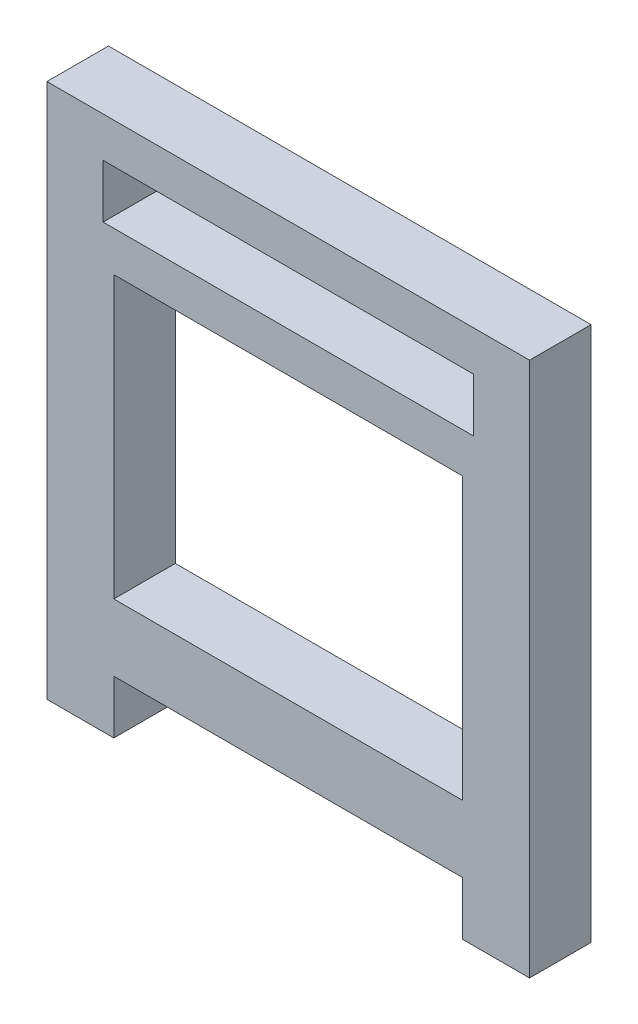
SolidWorks part; units mm, degrees
ref_plane "Front Plane" through (0, 0, 0) normal (0, 0, 1) x (1, 0, 0)
ref_plane "Top Plane" through (0, 0, 0) normal (0, 1, 0) x (1, 0, 0)
ref_plane "Right Plane" through (0, 0, 0) normal (1, 0, 0) x (0, 0, -1)
sketch "Sketch1" plane through (0, 0, 0) normal (0, 0, 1) x (1, 0, 0)
  line L0 (0, 0) -> (0, -2)
  line L1 (2.5, 0) -> (15.54, 0)
  line L2 (0, 0) -> (0, 18)
  line L3 (0, 18) -> (18.04, 18)
  line L4 (18.04, 0) -> (18.04, 18)
  line L5 (0, -2) -> (2.5, -2)
  line L6 (2.5, -2) -> (2.5, 0)
  line L7 (18.04, 0) -> (18.04, -2)
  line L8 (18.04, -2) -> (15.54, -2)
  line L9 (15.54, -2) -> (15.54, 0)
  line L12 (2.5, 2.5) -> (15.54, 2.5)
  line L13 (2.5, 2.5) -> (2.5, 13)
  line L14 (2.5, 13) -> (15.54, 13)
  line L15 (15.54, 2.5) -> (15.54, 13)
  line L16 (2.1, 14.5) -> (15.94, 14.5)
  line L17 (2.1, 14.5) -> (2.1, 16.5)
  line L18 (2.1, 16.5) -> (15.94, 16.5)
  line L19 (15.94, 14.5) -> (15.94, 16.5)
  dimension "D1" = 18
  dimension "D2" = 2.5
  dimension "D3" = 13.04
  dimension "D4" = 2
  dimension "D5" = 2
  dimension "D6" = 2.5
  dimension "D7" = 2.5
  dimension "D8" = 10.5
  dimension "D9" = 2
  dimension "D10" = 1.5
  dimension "D12" = 0.4
extrude "Boss-Extrude1" add sketch "Sketch1" along normal blind 2.3
